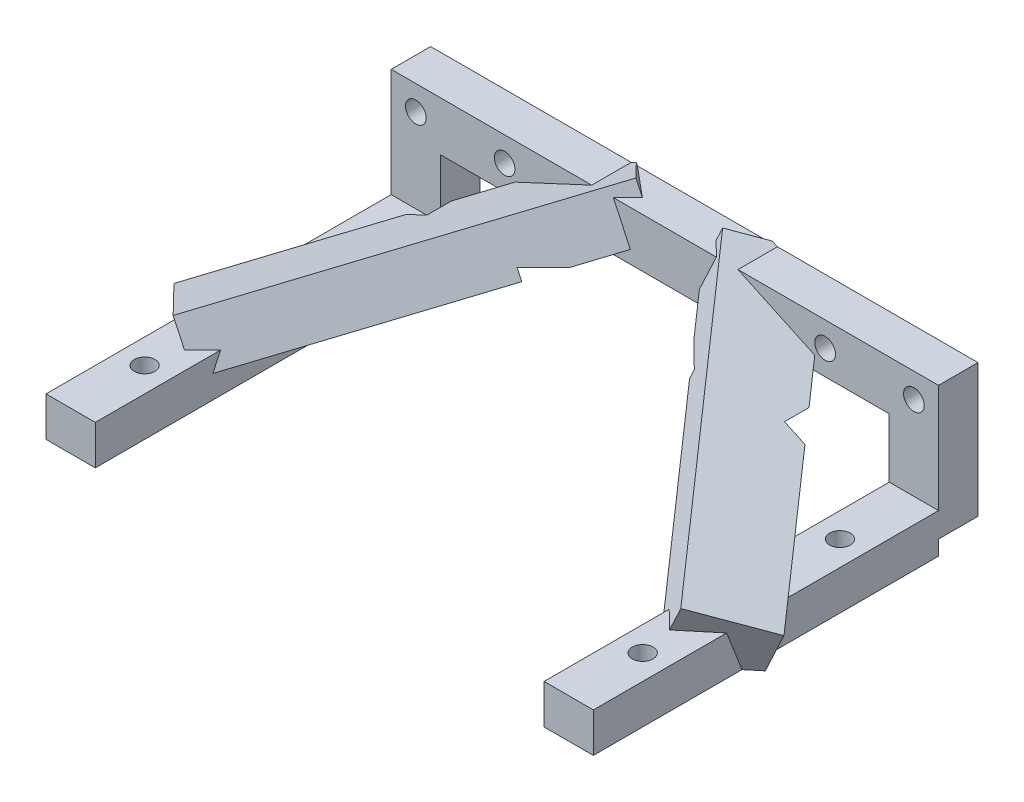
SolidWorks part; units mm, degrees
ref_plane "前视基准面" through (0, 0, 0) normal (0, 0, 1) x (1, 0, 0)
ref_plane "上视基准面" through (0, 0, 0) normal (0, 1, 0) x (1, 0, 0)
ref_plane "右视基准面" through (0, 0, 0) normal (1, 0, 0) x (0, 0, -1)
other "Configuration Table"
sketch "草图1" plane through (0, 0, 0) normal (0, 1, 0) x (1, 0, 0)
  line L0 (0, 83.3997) -> (0, -121.5112) construction
  line L1 (-137.493, 0) -> (143.9508, 0) construction
  line L14 (-50.5, 86.9698) -> (-50.5, -102.8788) construction
  line L15 (-55.5, 35) -> (-45.5, 35)
  line L16 (-45.5, 35) -> (-45.5, -35)
  line L17 (-55.5, 35) -> (-55.5, -35)
  line L18 (-55.5, -35) -> (-45.5, -35)
  line L19 (55.5, -35) -> (45.5, -35)
  line L20 (55.5, 35) -> (55.5, -35)
  line L21 (45.5, 35) -> (45.5, -35)
  line L22 (55.5, 35) -> (45.5, 35)
  circle A4 centre (-50.5, 20) radius 2.1
  circle A5 centre (-50.5, -20) radius 2.1
  circle A6 centre (50.5, -20) radius 2.1
  circle A7 centre (50.5, 20) radius 2.1
  point P13 (-50.5, 35)
  point P17 (-55.5, 0)
  point P18 (-45.5, 0)
  point P27 (45.5, 0)
  point P28 (55.5, 0)
  dimension "D1" = 50.5
  dimension "D2" = 4.2
  dimension "D3" = 20
  dimension "D4" = 10
  dimension "D5" = 15
extrude "凸台-拉伸1" add sketch "草图1" along normal blind 8
sketch "草图2" plane through (0, 0, 0) normal (0, 1, 0) x (1, 0, 0)
  line L0 (-45.5, 35) -> (-55.5, 35) construction
  line L1 (-45.5, 35) -> (-55.5, 35)
  line L2 (55.5, 35) -> (45.5, 35) construction
  line L3 (55.5, 35) -> (45.5, 35)
  line L4 (-55.5, 35) -> (-55.5, 43)
  line L5 (-55.5, 43) -> (-45.5, 43)
  line L6 (-45.5, 43) -> (-45.5, 35)
  line L7 (55.5, 35) -> (55.5, 43)
  line L8 (55.5, 43) -> (45.5, 43)
  line L9 (45.5, 43) -> (45.5, 35)
  point P6 (-50.5, 43)
  dimension "D1" = 8
extrude "凸台-拉伸2" add sketch "草图2" along normal blind 30
sketch "草图4" plane through (45.5, 0, 0) normal (-1, 0, 0) x (0, 0, 1)
  line L0 (-43, 30) -> (-43, 20)
  line L1 (-43, 30) -> (-43, 0) construction
  line L2 (-43, 20) -> (-35, 20)
  line L3 (-35, 30) -> (-35, 8) construction
  line L4 (-35, 20) -> (-35, 30)
  line L5 (-35, 30) -> (-43, 30)
  line L6 (-35, 8) -> (35, 8) construction
  dimension "D1" = 12
extrude "凸台-拉伸3" add sketch "草图4" along normal blind 97
sketch "草图6" plane through (0, 0, -43) normal (0, 0, -1) x (-1, 0, 0)
  line L0 (-69.7103, 25) -> (77.842, 25) construction
  line L2 (-55.5, 30) -> (55.5, 30) construction
  line L3 (50.5, 42.498) -> (50.5, -17.3792) construction
  line L4 (45.5, 0) -> (55.5, 0) construction
  line L5 (-50.5, 42.498) -> (-50.5, -17.3792) construction
  line L6 (-55.5, 0) -> (-45.5, 0) construction
  line L7 (0, 55.341) -> (0, -27.7706) construction
  circle A0 centre (-50.5, 25) radius 2.1
  circle A1 centre (-32.5, 25) radius 2.1
  circle A2 centre (32.5, 25) radius 2.1
  circle A3 centre (50.5, 25) radius 2.1
  point P8 (50.5, 0)
  point P13 (-50.5, 0)
  dimension "D2" = 4.2
  dimension "D3" = 4.2
  dimension "D1" = 5
  dimension "D4" = 18
extrude "切除-拉伸1" cut sketch "草图6" against normal through all
ref_plane "基准面1" through (-9.9126, 21.2577, 0) normal (-0.4226, 0.9063, 0) x (0, 0, 1)
sketch "草图9" plane through (-9.9126, 21.2577, 0) normal (-0.4226, 0.9063, 0) x (0, 0, 1)
  line L0 (7.9727, -46.9191) -> (-43, 0) construction
  line L3 (-35, -46.9191) -> (35, -46.9191) construction
  line L4 (-43, 62.9786) -> (-43, -37.6215) construction
  line L5 (13.2431, -41.1933) -> (-37.9228, 5.9037)
  line L6 (7.9727, -46.9191) -> (13.2431, -41.1933) construction
  line L7 (-37.9228, 5.9037) -> (-48.4637, -5.5479)
  line L8 (2.7022, -52.645) -> (-48.4637, -5.5479)
  line L9 (13.2431, -41.1933) -> (2.7022, -52.645)
extrude "凸台-拉伸4" add sketch "草图9" along normal blind 10
mirror "镜向2" about plane through (0, 0, 0) normal (1, 0, 0) of "凸台-拉伸4"
sketch "草图11" plane through (0, 0, 0) normal (0, 1, 0) x (1, 0, 0)
  line L5 (-55.5, 43) -> (55.5, 43)
  line L6 (55.5, 43) -> (55.5, 49)
  line L7 (55.5, 49) -> (-55.5, 49)
  line L8 (-55.5, 49) -> (-55.5, 43)
  dimension "D1" = 6
extrude "切除-拉伸3" cut sketch "草图11" along normal through all contours L6 L7 L8 L5
sketch "草图12" plane through (0, 0, -43) normal (0, 0, -1) x (-1, 0, 0)
  line L0 (-45.5, 20) -> (-45.5, 0)
  line L2 (45.5, 0) -> (45.5, 20)
  line L3 (45.5, 20) -> (-45.5, 20)
  line L4 (45.5, 0) -> (60, 0)
  line L5 (60, 0) -> (60, -5)
  line L6 (60, -5) -> (-60, -5)
  line L7 (-60, -5) -> (-60, 0)
  line L8 (-60, 0) -> (-45.5, 0)
  line L9 (0, 50.0791) -> (0, -34.5031) construction
  dimension "D1" = 60
  dimension "D2" = 60
  dimension "D3" = 5
extrude "切除-拉伸5" cut sketch "草图12" against normal blind 20
sketch "草图13" plane through (-55.5, 0, 0) normal (-1, 0, 0) x (0, 0, 1)
  line L0 (-43, 0) -> (-43, 3)
  line L1 (-43, 30) -> (-43, 0) construction
  line L2 (-43, 3) -> (-35, 3)
  line L3 (-35, 3) -> (-35, 0)
  line L4 (-43, 0) -> (0.1547, 0) construction
  line L5 (-35, 0) -> (-43, 0)
  dimension "D1" = 8
  dimension "D2" = 3
extrude "切除-拉伸7" cut sketch "草图13" against normal through all
sketch "草图14" plane through (0, 0, -43) normal (0, 0, -1) x (-1, 0, 0)
  line L0 (-65, 0) -> (65, 0)
  line L1 (-65, 0) -> (-65, -5)
  line L2 (-65, -5) -> (65, -5)
  line L3 (65, -5) -> (65, 0)
  line L4 (0, 44.2014) -> (0, -24.9956) construction
  dimension "D1" = 65
  dimension "D2" = 65
  dimension "D3" = 5
extrude "切除-拉伸8" cut sketch "草图14" against normal through all
sketch "草图15" plane through (0, 0, -43) normal (0, 0, -1) x (-1, 0, 0)
  circle A0 centre (50.5, 25) radius 2.1 construction
  circle A1 centre (32.5, 25) radius 2.1 construction
  circle A2 centre (-32.5, 25) radius 2.1 construction
  circle A3 centre (-50.5, 25) radius 2.1 construction
  circle A4 centre (50.5, 25) radius 2.1
  circle A5 centre (32.5, 25) radius 2.1
  circle A6 centre (-32.5, 25) radius 2.1
  circle A7 centre (-50.5, 25) radius 2.1
